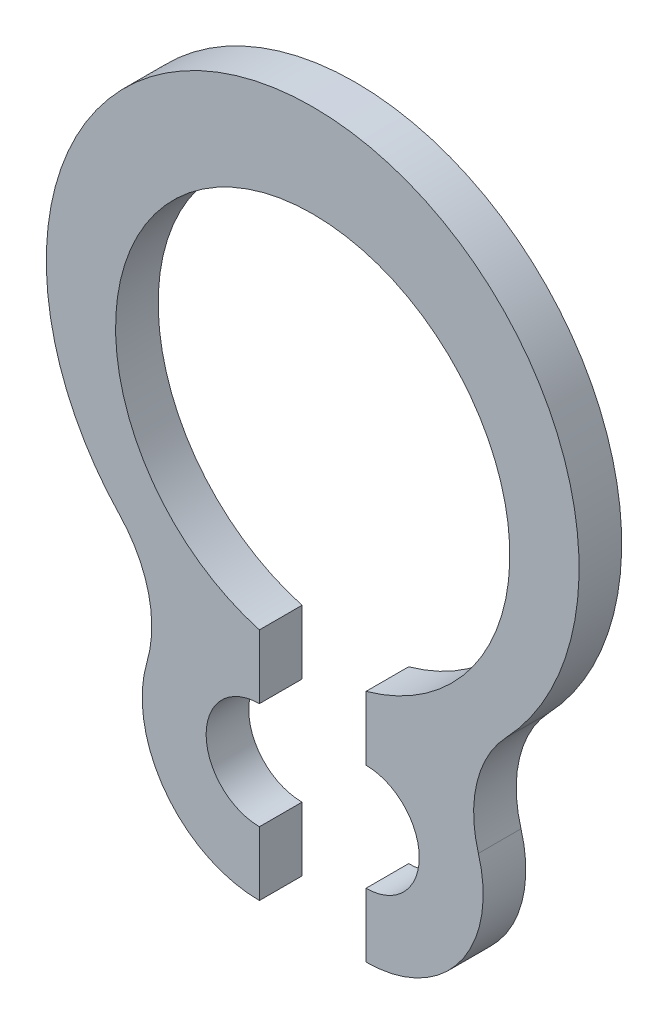
SolidWorks part; units mm, degrees
ref_plane "Front" through (0, 0, 0) normal (0, 0, 1) x (1, 0, 0)
ref_plane "Top" through (0, 0, 0) normal (0, 1, 0) x (1, 0, 0)
ref_plane "Right" through (0, 0, 0) normal (1, 0, 0) x (0, 0, -1)
sketch "Sketch1" plane through (0, 0, 0) normal (0, 0, 1) x (1, 0, 0)
  line L0 (0, -0.22) -> (0, -3.1859) construction
  line L1 (-0.5, -2.0012) -> (-0.5, -2.6012)
  line L2 (-0.5, -3.6012) -> (-0.5, -4.2012)
  line L3 (0.5, -3.6012) -> (0.5, -4.2012)
  line L4 (0.5, -2.0012) -> (0.5, -2.6012)
  arc A0 (0.5, -2.0012) -> (-0.5, -2.0012) centre (0, -0.22) ccw
  arc A1 (1.8127, -1.7217) -> (-1.8127, -1.7217) centre (0, 0) ccw
  arc A2 (-0.5, -2.6012) -> (-0.5, -3.6012) centre (-0.5, -3.1012) ccw
  arc A3 (-0.5, -4.2012) -> (-1.5551, -2.7902) centre (-0.5, -3.1012) cw
  arc A4 (-1.8127, -1.7217) -> (-1.5551, -2.7902) centre (-2.6103, -2.4792) cw
  arc A5 (1.8127, -1.7217) -> (1.5551, -2.7902) centre (2.6103, -2.4792) ccw
  arc A6 (0.5, -4.2012) -> (1.5551, -2.7902) centre (0.5, -3.1012) ccw
  arc A7 (0.5, -2.6012) -> (0.5, -3.6012) centre (0.5, -3.1012) cw
  dimension "d" = 3.7
  dimension "D0" = 5
  dimension "R3" = 1.25
  dimension "c" = 0.22
  dimension "B1" = 1
  dimension "d1" = 1
  dimension "D2" = 1
  dimension "h" = 1.1
extrude "Body" add sketch "Sketch1" against normal blind 0.4 separate body
equation "\"D2@Sketch1\" = \"d1@Sketch1\""
equation "\"R3@Sketch1\" = \"h@Sketch1\""
